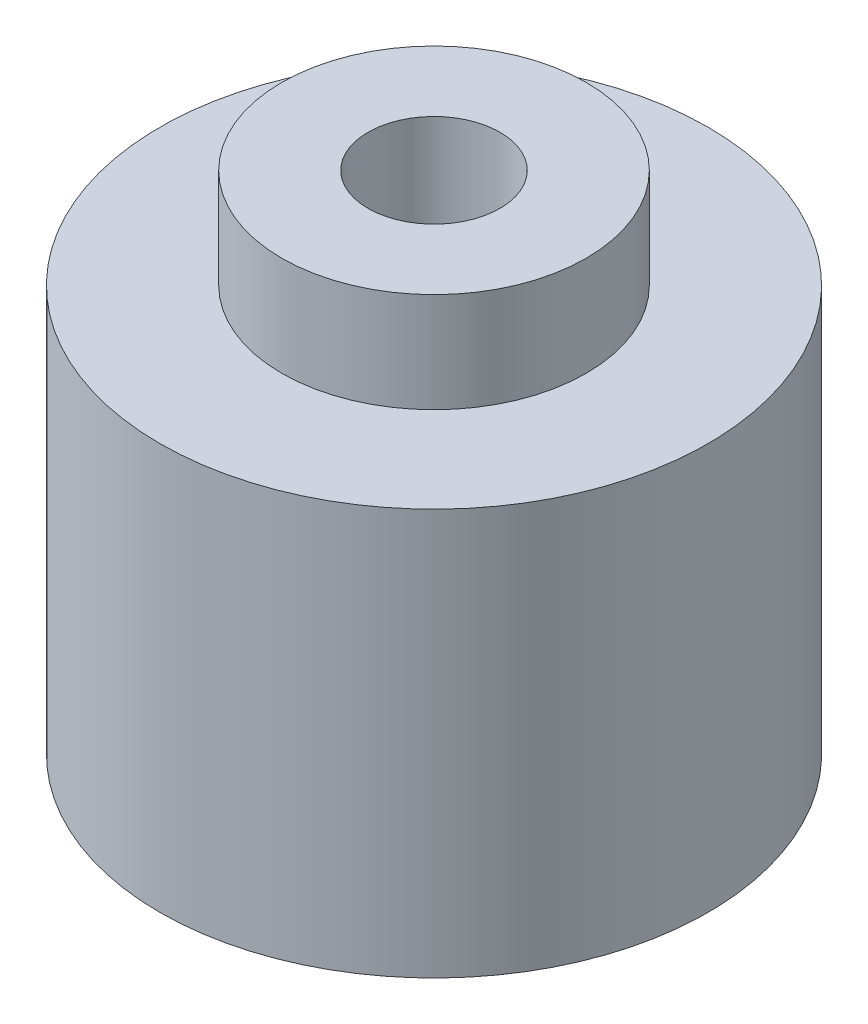
SolidWorks part; units mm, degrees
ref_plane "Front Plane" through (0, 0, 0) normal (0, 0, 1) x (1, 0, 0)
ref_plane "Top Plane" through (0, 0, 0) normal (0, 1, 0) x (1, 0, 0)
ref_plane "Right Plane" through (0, 0, 0) normal (1, 0, 0) x (0, 0, -1)
sketch "Sketch1" plane through (0, 0, 0) normal (0, 1, 0) x (1, 0, 0)
  circle A0 centre (0, 0) radius 27
extrude "Boss-Extrude1" add sketch "Sketch1" along normal blind 40
sketch "Sketch3" plane through (0, 40, 0) normal (0, 1, 0) x (1, 0, 0)
  circle A0 centre (0, 0) radius 15
extrude "Boss-Extrude2" add sketch "Sketch3" along normal blind 9.8189
sketch "Sketch4" plane through (0, 49.8189, 0) normal (0, 1, 0) x (1, 0, 0)
  circle A0 centre (0, 0) radius 6.5
extrude "Cut-Extrude3" cut sketch "Sketch4" against normal blind 55.1191
